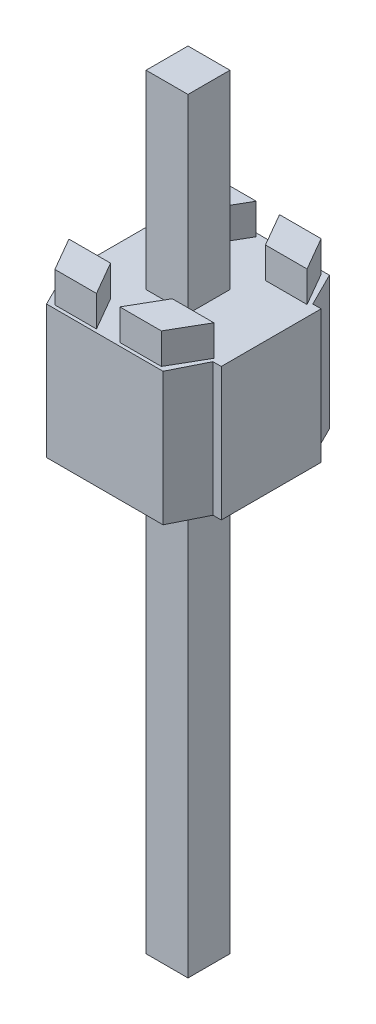
SolidWorks part; units mm, degrees
ref_plane "Front Plane" through (0, 0, 0) normal (0, 0, 1) x (1, 0, 0)
ref_plane "Top Plane" through (0, 0, 0) normal (0, 1, 0) x (1, 0, 0)
ref_plane "Right Plane" through (0, 0, 0) normal (1, 0, 0) x (0, 0, -1)
sketch "Sketch1" plane through (0, 0, 0) normal (0, 1, 0) x (1, 0, 0)
  line L0 (0, 1.5791) -> (0, -1.5527) construction
  line L2 (-0.32, 0.32) -> (0.32, 0.32)
  line L3 (-0.32, 0.32) -> (-0.32, -0.32)
  line L4 (-0.32, -0.32) -> (0.32, -0.32)
  line L5 (0.32, 0.32) -> (0.32, -0.32)
  line L6 (-0.32, 0.32) -> (0.32, -0.32) construction
  line L7 (-0.32, -0.32) -> (0.32, 0.32) construction
  line L8 (-1.143, 0.762) -> (-0.889, 1.27)
  line L9 (-0.889, 1.27) -> (0.889, 1.27)
  line L10 (0.889, 1.27) -> (1.143, 0.762)
  line L11 (1.143, 0.762) -> (1.27, 0.762)
  line L12 (1.27, 0.762) -> (1.27, -0.762)
  line L13 (1.27, -0.762) -> (1.143, -0.762)
  line L14 (1.143, -0.762) -> (0.889, -1.27)
  line L15 (0.889, -1.27) -> (-0.889, -1.27)
  line L16 (-0.889, -1.27) -> (-1.143, -0.762)
  line L17 (-1.143, -0.762) -> (-1.143, 0.762)
  line L18 (-1.7519, 0.762) -> (1.5375, 0.762) construction
  line L19 (1.0554, 0) -> (-1.5628, 0) construction
  line L20 (-1.697, -0.762) -> (2.4529, -0.762) construction
  point P3 (0, 0)
  dimension "D1" = 0.64
  dimension "D2" = 0.64
  dimension "D3" = 0.889
  dimension "D4" = 1.778
  dimension "D5" = 1.27
  dimension "D6" = 1.143
  dimension "D7" = 0.762
  dimension "D8" = 1.27
extrude "Boss-Extrude1" add sketch "Sketch1" along normal blind 1.48 and the other way blind 1.02
sketch "Sketch2" plane through (0, 1.48, 0) normal (0, 1, 0) x (1, 0, 0)
  line L0 (-1.1061, -0.7112) -> (-0.4711, -0.7112)
  line L1 (-0.4711, -0.7112) -> (-0.1778, -1.2192)
  line L2 (-0.1778, -1.2192) -> (-0.8128, -1.2192)
  line L5 (-0.8128, -1.2192) -> (-1.1061, -0.7112)
  line L6 (0, 1.3694) -> (0, -1.4569) construction
  line L7 (-1.5186, 0) -> (1.896, 0) construction
  line L8 (-0.8128, 1.2192) -> (-1.1061, 0.7112)
  line L9 (-0.1778, 1.2192) -> (-0.8128, 1.2192)
  line L10 (-0.4711, 0.7112) -> (-0.1778, 1.2192)
  line L11 (-1.1061, 0.7112) -> (-0.4711, 0.7112)
  line L12 (1.1061, 0.7112) -> (0.4711, 0.7112)
  line L13 (0.4711, 0.7112) -> (0.1778, 1.2192)
  line L14 (0.1778, 1.2192) -> (0.8128, 1.2192)
  line L15 (0.8128, 1.2192) -> (1.1061, 0.7112)
  line L16 (0.8128, -1.2192) -> (1.1061, -0.7112)
  line L17 (0.1778, -1.2192) -> (0.8128, -1.2192)
  line L18 (0.4711, -0.7112) -> (0.1778, -1.2192)
  line L19 (1.1061, -0.7112) -> (0.4711, -0.7112)
extrude "Cut-Extrude2" cut sketch "Sketch2" against normal blind 0.47 flip side to cut
sketch "Sketch3" plane through (0, 1.01, 0) normal (0, 1, 0) x (1, 0, 0)
  line L0 (-0.32, 0.32) -> (0.32, 0.32) construction
  line L1 (0.32, 0.32) -> (0.32, -0.32) construction
  line L2 (0.32, -0.32) -> (-0.32, -0.32) construction
  line L3 (-0.32, -0.32) -> (-0.32, 0.32) construction
  line L4 (-0.32, 0.32) -> (0.32, 0.32)
  line L5 (0.32, 0.32) -> (0.32, -0.32)
  line L6 (0.32, -0.32) -> (-0.32, -0.32)
  line L7 (-0.32, -0.32) -> (-0.32, 0.32)
extrude "Boss-Extrude2" add sketch "Sketch3" along normal blind 2.9 separate body
sketch "Sketch4" plane through (0, -1.02, 0) normal (0, -1, 0) x (1, 0, 0)
  line L4 (-0.32, -0.32) -> (0.32, -0.32)
  line L5 (0.32, -0.32) -> (0.32, 0.32)
  line L6 (0.32, 0.32) -> (-0.32, 0.32)
  line L7 (-0.32, 0.32) -> (-0.32, -0.32)
  line L8 (-0.32, -0.32) -> (0.32, -0.32)
  line L9 (0.32, -0.32) -> (0.32, 0.32)
  line L10 (0.32, 0.32) -> (-0.32, 0.32)
  line L11 (-0.32, 0.32) -> (-0.32, -0.32)
  dimension "D1" = 0
extrude "Boss-Extrude3" add sketch "Sketch4" along normal blind 6.75 separate body
